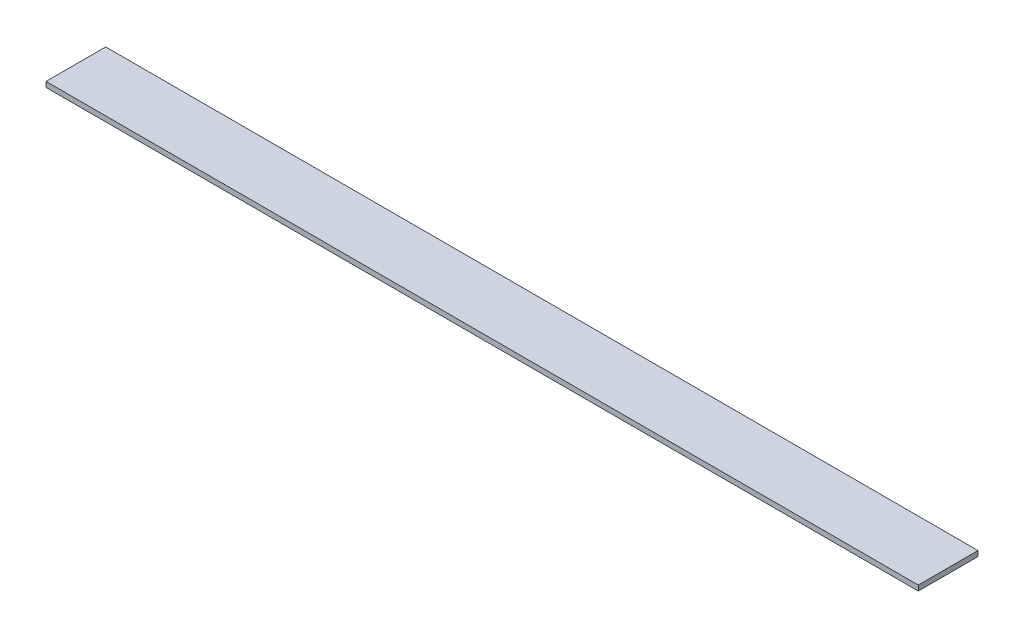
SolidWorks part; units mm, degrees
ref_plane "Front Plane" through (0, 0, 0) normal (0, 0, 1) x (1, 0, 0)
ref_plane "Top Plane" through (0, 0, 0) normal (0, 1, 0) x (1, 0, 0)
ref_plane "Right Plane" through (0, 0, 0) normal (1, 0, 0) x (0, 0, -1)
sketch "Sketch1" plane through (0, 0, 0) normal (0, 1, 0) x (1, 0, 0)
  line L1 (-29.7677, -9.8564) -> (233.2323, -9.8564)
  line L2 (-29.7677, -9.8564) -> (-29.7677, 8.1436)
  line L3 (-29.7677, 8.1436) -> (233.2323, 8.1436)
  line L4 (233.2323, -9.8564) -> (233.2323, 8.1436)
  dimension "D1" = 18
  dimension "D2" = 263
extrude "Boss-Extrude1" add sketch "Sketch1" along normal blind 1.5748
